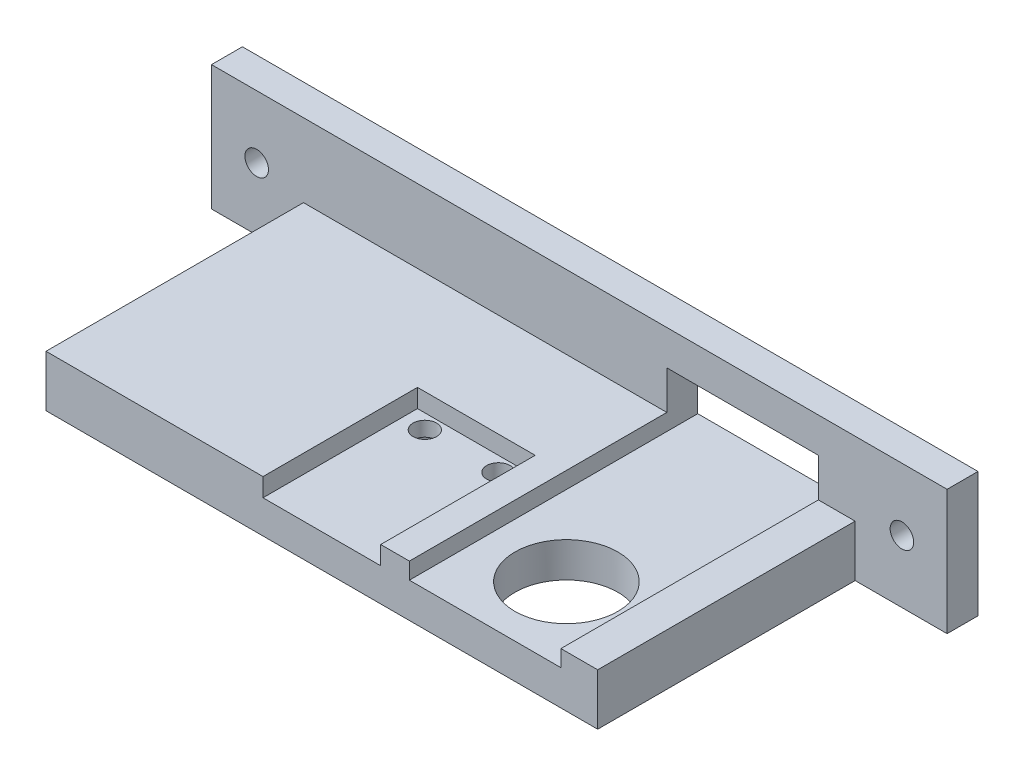
SolidWorks part; units mm, degrees
ref_plane "Front Plane" through (0, 0, 0) normal (0, 0, 1) x (1, 0, 0)
ref_plane "Top Plane" through (0, 0, 0) normal (0, 1, 0) x (1, 0, 0)
ref_plane "Right Plane" through (0, 0, 0) normal (1, 0, 0) x (0, 0, -1)
sketch "Sketch1" plane through (0, 0, 0) normal (0, 1, 0) x (1, 0, 0)
  line L0 (-37.5, -10.5) -> (37.5, -10.5)
  line L1 (-50, 10.5) -> (50, 10.5)
  line L2 (-50, 10.5) -> (-50, -10.5)
  line L3 (-50, -10.5) -> (50, -10.5)
  line L4 (50, 10.5) -> (50, -10.5)
  line L5 (-50, 10.5) -> (50, -10.5) construction
  line L6 (-50, -10.5) -> (50, 10.5) construction
  line L8 (-37.5, -10.5) -> (37.5, -10.5)
  line L9 (-37.5, -10.5) -> (-37.5, 6.2981)
  line L10 (-37.5, 6.2981) -> (37.5, 6.2981)
  line L11 (37.5, -10.5) -> (37.5, 6.2981)
  line L12 (-50, 10.5) -> (50, 10.5)
  line L13 (-50, 10.5) -> (-50, 6.2981)
  line L14 (-50, 6.2981) -> (50, 6.2981)
  line L15 (50, 10.5) -> (50, 6.2981)
  line L16 (37.5, 6.2981) -> (-37.5, 6.2981)
  line L17 (37.5, 6.2981) -> (37.5, -28.7019)
  line L18 (37.5, -28.7019) -> (-37.5, -28.7019)
  line L19 (-37.5, 6.2981) -> (-37.5, -28.7019)
  point P0 (0, 0)
  point P9 (0, -10.5)
  dimension "D1" = 100
  dimension "D2" = 21
  dimension "D3" = 75
  dimension "D4" = 16.7981
  dimension "D5" = 35
extrude "body" add sketch "Sketch1" along normal blind 7 contours L2 L14 L10 L4 L1 | L0 L11 L10 L9 | L17 L16 L19 L18
sketch "Sketch3" plane through (0, 7, 0) normal (0, 1, 0) x (1, 0, 0)
  line L0 (0, 10.5) -> (0, -28.7019) construction
  line L1 (-50, 10.5) -> (50, 10.5) construction
  line L2 (37.5, -28.7019) -> (-37.5, -28.7019) construction
  line L3 (0, -28.7019) -> (0, -7.7019) construction
  line L4 (8, -7.7019) -> (-8, -7.7019)
  line L6 (-8, -7.7019) -> (8, -7.7019)
  line L7 (-8, -7.7019) -> (-8, -28.7019)
  line L8 (-8, -28.7019) -> (8, -28.7019)
  line L9 (8, -7.7019) -> (8, -28.7019)
  point P10 (0, -7.7019)
  line M11 (-37.5, -28.7019) -> (37.5, -28.7019)
  dimension "D1" = 21
  dimension "D2" = 16
extrude "chip-divet" cut sketch "Sketch3" against normal blind 2.5 contours L9 L4 L7 M11
sketch "Sketch4" plane through (0, 4.5, 0) normal (0, 1, 0) x (1, 0, 0)
  line L0 (0, -7.7019) -> (0, -9.7019) construction
  line L1 (8, -7.7019) -> (-8, -7.7019) construction
  line L2 (5, -9.7019) -> (-5, -9.7019) construction
  circle A0 centre (-5, -9.7019) radius 1.6
  circle A1 centre (5, -9.7019) radius 1.6
  point P8 (0, -9.7019)
  dimension "D3" = 3.2
  dimension "D4" = 3.2
  dimension "D1" = 2
  dimension "D2" = 10
extrude "chip-mounting-holes" cut sketch "Sketch4" against normal through all
sketch "Sketch5" plane through (0, 0, 0) normal (0, -1, 0) x (1, 0, 0)
  line L1 (6.2117, 12.5553) -> (3.1348, 12.178)
  line L2 (3.1348, 12.178) -> (1.923, 9.3246)
  line L3 (1.923, 9.3246) -> (3.7883, 6.8485)
  line L4 (3.7883, 6.8485) -> (6.8652, 7.2259)
  line L5 (6.8652, 7.2259) -> (8.077, 10.0792)
  line L6 (8.077, 10.0792) -> (6.2117, 12.5553)
  line L7 (-3.7883, 12.5553) -> (-6.8652, 12.178)
  line L8 (-6.8652, 12.178) -> (-8.077, 9.3246)
  line L9 (-8.077, 9.3246) -> (-6.2117, 6.8485)
  line L10 (-6.2117, 6.8485) -> (-3.1348, 7.2259)
  line L11 (-3.1348, 7.2259) -> (-1.923, 10.0792)
  line L12 (-1.923, 10.0792) -> (-3.7883, 12.5553)
  circle A0 centre (5, 9.7019) radius 2.6847 construction
  circle A1 centre (-5, 9.7019) radius 2.6847 construction
  dimension "D1" = 6.2
  dimension "D2" = 6.2
extrude "chip-captive-nuts" cut sketch "Sketch5" against normal blind 2.5
sketch "Sketch6" plane through (0, 7, 0) normal (0, 1, 0) x (1, 0, 0)
  line L1 (37.5, -28.7019) -> (8, -28.7019)
  line L2 (37.5, -28.7019) -> (37.5, -7.7019)
  line L3 (37.5, -7.7019) -> (8, -7.7019)
  line L4 (8, -28.7019) -> (8, -7.7019)
  circle A0 centre (22.75, -18.2019) radius 7
  dimension "D1" = 14
extrude "routing-hole" cut sketch "Sketch6" against normal through all contours A0
sketch "Sketch7" plane through (0, 7, 0) normal (0, 1, 0) x (1, 0, 0)
  line L1 (50, 6.2981) -> (-50, 6.2981)
  line L2 (50, 6.2981) -> (50, 10.5)
  line L3 (50, 10.5) -> (-50, 10.5)
  line L4 (-50, 6.2981) -> (-50, 10.5)
extrude "face-plate" add sketch "Sketch7" along normal blind 10
sketch "Sketch8" plane through (0, 0, -10.5) normal (0, 0, -1) x (-1, 0, 0)
  line L0 (0, 17) -> (0, 0) construction
  line L1 (-50, 17) -> (50, 17) construction
  line L2 (50, 0) -> (-50, 0) construction
  line L3 (-32.5, 17) -> (32.5, 17) construction
  line L4 (-32.5, 17) -> (-32.5, 12.25) construction
  line L6 (-32.5, 12.25) -> (-11.9, 12.25)
  line L7 (-32.5, 12.25) -> (-32.5, 4.75)
  line L8 (-32.5, 4.75) -> (-11.9, 4.75)
  line L9 (-11.9, 12.25) -> (-11.9, 4.75)
  point P9 (0, 17)
  dimension "D1" = 65
  dimension "D2" = 4.75
  dimension "D3" = 20.6
  dimension "D4" = 7.5
extrude "switch-hole" cut sketch "Sketch8" against normal through all
sketch "Sketch2" plane through (0, 0, -10.5) normal (0, 0, -1) x (-1, 0, 0)
  line L0 (-50, 8.5) -> (-43.86, 8.5)
  line L1 (-50, 17) -> (-50, 0) construction
  line L2 (50, 8.5) -> (43.86, 8.5)
  line L3 (50, 17) -> (50, 0) construction
  circle A0 centre (-43.86, 8.5) radius 1.6
  circle A1 centre (43.86, 8.5) radius 1.6
  dimension "D3" = 3.2
  dimension "D4" = 3.2
  dimension "D1" = 6.14
  dimension "D2" = 6.14
extrude "mounting-holes" cut sketch "Sketch2" against normal through all
